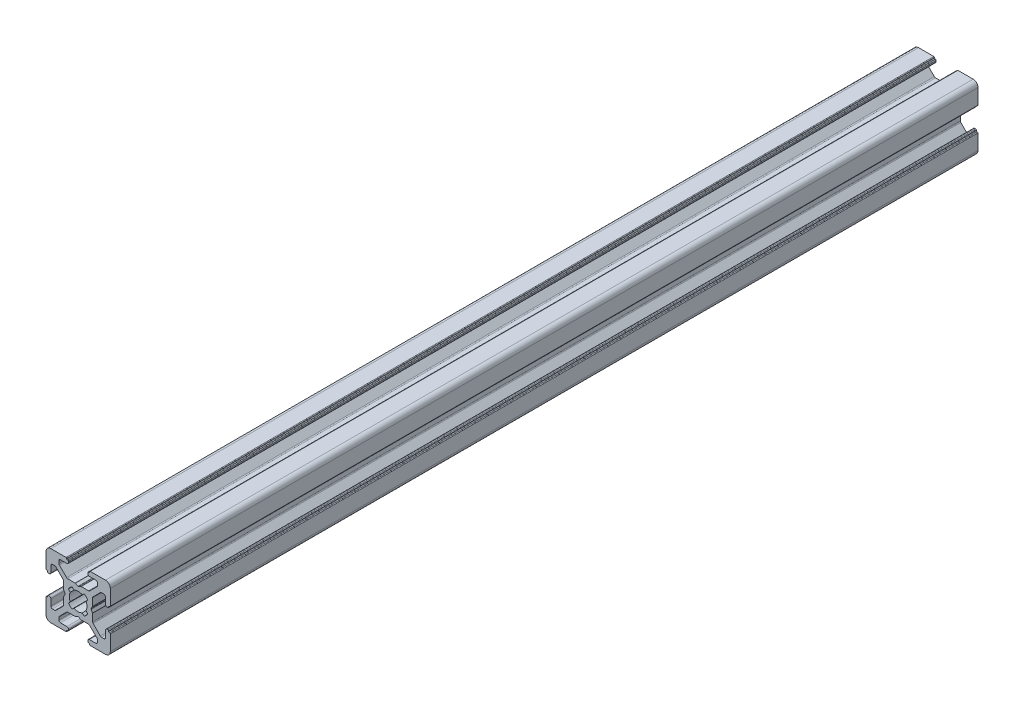
SolidWorks part; units mm, degrees
ref_plane "Front Plane" through (0, 0, 0) normal (0, 0, 1) x (1, 0, 0)
ref_plane "Top Plane" through (0, 0, 0) normal (0, 1, 0) x (1, 0, 0)
ref_plane "Right Plane" through (0, 0, 0) normal (1, 0, 0) x (0, 0, -1)
sketch "Sketch1" plane through (0, 0, 0) normal (0, 0, 1) x (1, 0, 0)
  line L0 (0, 13.3675) -> (0, -10.9159) construction
  line L1 (-12.9725, 0) -> (15.1887, 0) construction
  line L2 (-3.5, 8.5) -> (-5.5, 8.5)
  line L3 (-3.55, 9.7) -> (-3.55, 9.8)
  line L4 (-6, 7.2678) -> (-6, 8)
  line L5 (-7.2678, 6) -> (-8, 6)
  line L6 (-3.75, 10) -> (-8.5, 10)
  line L7 (-9.7, 3.55) -> (-9.8, 3.55)
  line L8 (-9.5, 3.2) -> (-9.5, 3.35)
  line L9 (-9, 3) -> (-9.3, 3)
  line L10 (-4.4732, 0.8536) -> (-4.0381, 0.1)
  line L11 (-4.5, 3.2322) -> (-4.5, 0.9536)
  line L12 (-8.5, 3.5) -> (-8.5, 5.5)
  line L13 (-10, 3.75) -> (-10, 8.5)
  line L14 (-3.5858, 4.6464) -> (-5.8536, 6.9142)
  line L15 (-4.6464, 3.5858) -> (-6.9142, 5.8536)
  line L16 (-3.2, 9.5) -> (-3.35, 9.5)
  line L17 (-3, 9) -> (-3, 9.3)
  line L18 (-0.8536, 4.4732) -> (-0.1, 4.0381)
  line L19 (-3.2322, 4.5) -> (-0.9536, 4.5)
  line L20 (-1.2582, 2.4453) -> (-1.9139, 2.9896)
  line L21 (-2.4453, 1.2582) -> (-2.9922, 1.9099)
  line L22 (3.5, -8.5) -> (5.5, -8.5)
  line L23 (3.55, -9.7) -> (3.55, -9.8)
  line L24 (6, -7.2678) -> (6, -8)
  line L25 (7.2678, -6) -> (8, -6)
  line L26 (3.75, -10) -> (8.5, -10)
  line L27 (9.7, -3.55) -> (9.8, -3.55)
  line L28 (9.5, -3.2) -> (9.5, -3.35)
  line L29 (9, -3) -> (9.3, -3)
  line L30 (4.4732, -0.8536) -> (4.0381, -0.1)
  line L31 (4.5, -3.2322) -> (4.5, -0.9536)
  line L32 (8.5, -3.5) -> (8.5, -5.5)
  line L33 (10, -3.75) -> (10, -8.5)
  line L34 (3.5858, -4.6464) -> (5.8536, -6.9142)
  line L35 (4.6464, -3.5858) -> (6.9142, -5.8536)
  line L36 (3.2, -9.5) -> (3.35, -9.5)
  line L37 (3, -9) -> (3, -9.3)
  line L38 (0.8536, -4.4732) -> (0.1, -4.0381)
  line L39 (3.2322, -4.5) -> (0.9536, -4.5)
  line L40 (1.2582, -2.4453) -> (1.9139, -2.9896)
  line L41 (2.4453, -1.2582) -> (2.9922, -1.9099)
  line L42 (-2.4453, -1.2582) -> (-2.9922, -1.9099)
  line L43 (-1.2582, -2.4453) -> (-1.9139, -2.9896)
  line L44 (-3.2322, -4.5) -> (-0.9536, -4.5)
  line L45 (-0.8536, -4.4732) -> (-0.1, -4.0381)
  line L46 (-3, -9) -> (-3, -9.3)
  line L47 (-3.2, -9.5) -> (-3.35, -9.5)
  line L48 (-4.6464, -3.5858) -> (-6.9142, -5.8536)
  line L49 (-3.5858, -4.6464) -> (-5.8536, -6.9142)
  line L50 (-10, -3.75) -> (-10, -8.5)
  line L51 (-8.5, -3.5) -> (-8.5, -5.5)
  line L52 (-4.5, -3.2322) -> (-4.5, -0.9536)
  line L53 (-4.4732, -0.8536) -> (-4.0381, -0.1)
  line L54 (-9, -3) -> (-9.3, -3)
  line L55 (-9.5, -3.2) -> (-9.5, -3.35)
  line L56 (-9.7, -3.55) -> (-9.8, -3.55)
  line L57 (2.4453, 1.2582) -> (2.9922, 1.9099)
  line L58 (1.2582, 2.4453) -> (1.9139, 2.9896)
  line L59 (3.2322, 4.5) -> (0.9536, 4.5)
  line L60 (0.8536, 4.4732) -> (0.1, 4.0381)
  line L61 (-3.75, -10) -> (-8.5, -10)
  line L62 (-7.2678, -6) -> (-8, -6)
  line L63 (-6, -7.2678) -> (-6, -8)
  line L64 (3, 9) -> (3, 9.3)
  line L65 (3.2, 9.5) -> (3.35, 9.5)
  line L66 (4.6464, 3.5858) -> (6.9142, 5.8536)
  line L67 (3.5858, 4.6464) -> (5.8536, 6.9142)
  line L68 (10, 3.75) -> (10, 8.5)
  line L69 (8.5, 3.5) -> (8.5, 5.5)
  line L70 (4.5, 3.2322) -> (4.5, 0.9536)
  line L71 (4.4732, 0.8536) -> (4.0381, 0.1)
  line L72 (9, 3) -> (9.3, 3)
  line L73 (9.5, 3.2) -> (9.5, 3.35)
  line L74 (9.7, 3.55) -> (9.8, 3.55)
  line L75 (3.75, 10) -> (8.5, 10)
  line L76 (7.2678, 6) -> (8, 6)
  line L77 (6, 7.2678) -> (6, 8)
  line L78 (3.55, 9.7) -> (3.55, 9.8)
  line L79 (3.5, 8.5) -> (5.5, 8.5)
  line L80 (-3.55, -9.7) -> (-3.55, -9.8)
  line L81 (-3.5, -8.5) -> (-5.5, -8.5)
  arc A0 (-10, 8.5) -> (-8.5, 10) centre (-8.5, 8.5) cw
  arc A1 (-8.5, 5.5) -> (-8, 6) centre (-8, 5.5) cw
  arc A2 (-7.2678, 6) -> (-6.9142, 5.8536) centre (-7.2678, 5.5) cw
  arc A3 (-5.8536, 6.9142) -> (-6, 7.2678) centre (-5.5, 7.2678) cw
  arc A4 (-6, 8) -> (-5.5, 8.5) centre (-5.5, 8) cw
  arc A5 (-9.7, 3.55) -> (-9.5, 3.35) centre (-9.7, 3.35) cw
  arc A6 (-9.8, 3.55) -> (-10, 3.75) centre (-9.8, 3.75) cw
  arc A7 (-9.3, 3) -> (-9.5, 3.2) centre (-9.3, 3.2) cw
  arc A8 (-8.5, 3.5) -> (-9, 3) centre (-9, 3.5) cw
  arc A9 (-4.6464, 3.5858) -> (-4.5, 3.2322) centre (-5, 3.2322) cw
  arc A10 (-4.4732, 0.8536) -> (-4.5, 0.9536) centre (-4.3, 0.9536) cw
  arc A11 (-4.0381, 0.1) -> (-4.0381, -0.1) centre (-4.2113, 0) cw
  arc A12 (-3.2, 9.5) -> (-3, 9.3) centre (-3.2, 9.3) cw
  arc A13 (-0.9536, 4.5) -> (-0.8536, 4.4732) centre (-0.9536, 4.3) cw
  arc A14 (-2.9922, 1.9099) -> (-1.9139, 2.9896) centre (0, 0) cw
  arc A15 (-3.2322, 4.5) -> (-3.5858, 4.6464) centre (-3.2322, 5) cw
  arc A16 (-3.75, 10) -> (-3.55, 9.8) centre (-3.75, 9.8) cw
  arc A17 (-3.35, 9.5) -> (-3.55, 9.7) centre (-3.35, 9.7) cw
  arc A18 (2.4453, -1.2582) -> (2.4453, 1.2582) centre (0, 0) ccw
  arc A19 (-3, 9) -> (-3.5, 8.5) centre (-3.5, 9) cw
  arc A20 (-2.4453, -1.2582) -> (-2.4453, 1.2582) centre (0, 0) cw
  arc A21 (10, -8.5) -> (8.5, -10) centre (8.5, -8.5) cw
  arc A22 (8.5, -5.5) -> (8, -6) centre (8, -5.5) cw
  arc A23 (7.2678, -6) -> (6.9142, -5.8536) centre (7.2678, -5.5) cw
  arc A24 (5.8536, -6.9142) -> (6, -7.2678) centre (5.5, -7.2678) cw
  arc A25 (6, -8) -> (5.5, -8.5) centre (5.5, -8) cw
  arc A26 (9.7, -3.55) -> (9.5, -3.35) centre (9.7, -3.35) cw
  arc A27 (9.8, -3.55) -> (10, -3.75) centre (9.8, -3.75) cw
  arc A28 (9.3, -3) -> (9.5, -3.2) centre (9.3, -3.2) cw
  arc A29 (8.5, -3.5) -> (9, -3) centre (9, -3.5) cw
  arc A30 (4.6464, -3.5858) -> (4.5, -3.2322) centre (5, -3.2322) cw
  arc A31 (4.4732, -0.8536) -> (4.5, -0.9536) centre (4.3, -0.9536) cw
  arc A32 (3.2, -9.5) -> (3, -9.3) centre (3.2, -9.3) cw
  arc A33 (-0.1, -4.0381) -> (0.1, -4.0381) centre (0, -4.2113) cw
  arc A34 (0.9536, -4.5) -> (0.8536, -4.4732) centre (0.9536, -4.3) cw
  arc A35 (2.9922, -1.9099) -> (1.9139, -2.9896) centre (0, 0) cw
  arc A36 (1.2582, -2.4453) -> (-1.2582, -2.4453) centre (0, 0) cw
  arc A37 (3.2322, -4.5) -> (3.5858, -4.6464) centre (3.2322, -5) cw
  arc A38 (3.75, -10) -> (3.55, -9.8) centre (3.75, -9.8) cw
  arc A39 (3.35, -9.5) -> (3.55, -9.7) centre (3.35, -9.7) cw
  arc A40 (3, -9) -> (3.5, -8.5) centre (3.5, -9) cw
  arc A41 (-3, -9) -> (-3.5, -8.5) centre (-3.5, -9) ccw
  arc A42 (-3.35, -9.5) -> (-3.55, -9.7) centre (-3.35, -9.7) ccw
  arc A43 (-3.75, -10) -> (-3.55, -9.8) centre (-3.75, -9.8) ccw
  arc A44 (-3.2322, -4.5) -> (-3.5858, -4.6464) centre (-3.2322, -5) ccw
  arc A45 (-2.9922, -1.9099) -> (-1.9139, -2.9896) centre (0, 0) ccw
  arc A46 (-0.9536, -4.5) -> (-0.8536, -4.4732) centre (-0.9536, -4.3) ccw
  arc A47 (-3.2, -9.5) -> (-3, -9.3) centre (-3.2, -9.3) ccw
  arc A48 (-4.4732, -0.8536) -> (-4.5, -0.9536) centre (-4.3, -0.9536) ccw
  arc A49 (3, 9) -> (3.5, 8.5) centre (3.5, 9) ccw
  arc A50 (3.35, 9.5) -> (3.55, 9.7) centre (3.35, 9.7) ccw
  arc A51 (3.75, 10) -> (3.55, 9.8) centre (3.75, 9.8) ccw
  arc A52 (3.2322, 4.5) -> (3.5858, 4.6464) centre (3.2322, 5) ccw
  arc A53 (1.2582, 2.4453) -> (-1.2582, 2.4453) centre (0, 0) ccw
  arc A54 (-4.6464, -3.5858) -> (-4.5, -3.2322) centre (-5, -3.2322) ccw
  arc A55 (-8.5, -3.5) -> (-9, -3) centre (-9, -3.5) ccw
  arc A56 (-9.3, -3) -> (-9.5, -3.2) centre (-9.3, -3.2) ccw
  arc A57 (-9.8, -3.55) -> (-10, -3.75) centre (-9.8, -3.75) ccw
  arc A58 (-9.7, -3.55) -> (-9.5, -3.35) centre (-9.7, -3.35) ccw
  arc A59 (-6, -8) -> (-5.5, -8.5) centre (-5.5, -8) ccw
  arc A60 (2.9922, 1.9099) -> (1.9139, 2.9896) centre (0, 0) ccw
  arc A61 (0.9536, 4.5) -> (0.8536, 4.4732) centre (0.9536, 4.3) ccw
  arc A62 (-0.1, 4.0381) -> (0.1, 4.0381) centre (0, 4.2113) ccw
  arc A63 (-5.8536, -6.9142) -> (-6, -7.2678) centre (-5.5, -7.2678) ccw
  arc A64 (-7.2678, -6) -> (-6.9142, -5.8536) centre (-7.2678, -5.5) ccw
  arc A65 (-8.5, -5.5) -> (-8, -6) centre (-8, -5.5) ccw
  arc A66 (-10, -8.5) -> (-8.5, -10) centre (-8.5, -8.5) ccw
  arc A67 (3.2, 9.5) -> (3, 9.3) centre (3.2, 9.3) ccw
  arc A68 (4.0381, 0.1) -> (4.0381, -0.1) centre (4.2113, 0) ccw
  arc A69 (4.4732, 0.8536) -> (4.5, 0.9536) centre (4.3, 0.9536) ccw
  arc A70 (4.6464, 3.5858) -> (4.5, 3.2322) centre (5, 3.2322) ccw
  arc A71 (8.5, 3.5) -> (9, 3) centre (9, 3.5) ccw
  arc A72 (9.3, 3) -> (9.5, 3.2) centre (9.3, 3.2) ccw
  arc A73 (9.8, 3.55) -> (10, 3.75) centre (9.8, 3.75) ccw
  arc A74 (9.7, 3.55) -> (9.5, 3.35) centre (9.7, 3.35) ccw
  arc A75 (6, 8) -> (5.5, 8.5) centre (5.5, 8) ccw
  arc A76 (5.8536, 6.9142) -> (6, 7.2678) centre (5.5, 7.2678) ccw
  arc A77 (7.2678, 6) -> (6.9142, 5.8536) centre (7.2678, 5.5) ccw
  arc A78 (8.5, 5.5) -> (8, 6) centre (8, 5.5) ccw
  arc A79 (10, 8.5) -> (8.5, 10) centre (8.5, 8.5) ccw
  dimension "D4" = 5.5
  dimension "D1" = 6
  dimension "D2" = 20
  dimension "D3" = 20
  dimension "D5" = 5.5
  dimension "D6" = 10
  dimension "D7" = 6
  dimension "D8" = 6
  dimension "D9" = 6
extrude "Extrude1" add sketch "Sketch1" along normal blind 270
